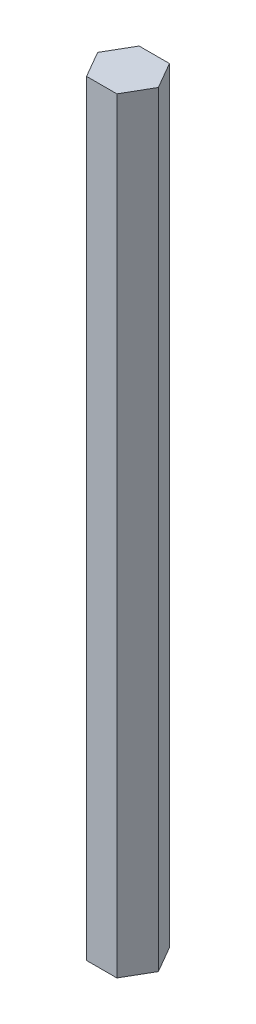
SolidWorks part; units mm, degrees
ref_plane "Alzado" through (0, 0, 0) normal (0, 0, 1) x (1, 0, 0)
ref_plane "Planta" through (0, 0, 0) normal (0, 1, 0) x (1, 0, 0)
ref_plane "Vista lateral" through (0, 0, 0) normal (1, 0, 0) x (0, 0, -1)
sketch "Croquis1" plane through (0, 0, 0) normal (0, 1, 0) x (1, 0, 0)
  line L1 (7.3323, 0) -> (3.6662, 6.35)
  line L2 (3.6662, 6.35) -> (-3.6662, 6.35)
  line L3 (-3.6662, 6.35) -> (-7.3323, 0)
  line L4 (-7.3323, 0) -> (-3.6662, -6.35)
  line L5 (-3.6662, -6.35) -> (3.6662, -6.35)
  line L6 (3.6662, -6.35) -> (7.3323, 0)
  circle A0 centre (0, 0) radius 6.35 construction
  dimension "D1" = 12.7
extrude "Saliente-Extruir1" add sketch "Croquis1" along normal blind 185
